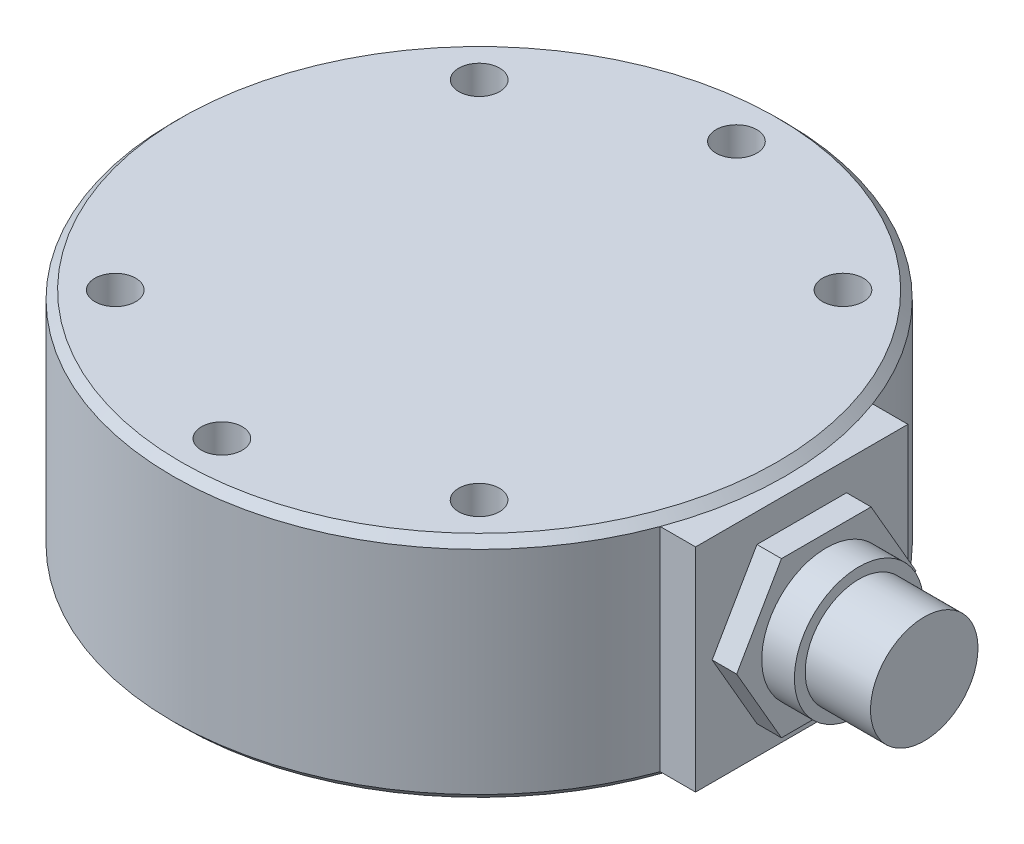
SolidWorks part; units mm, degrees
ref_plane "Front Plane" through (0, 0, 0) normal (0, 0, 1) x (1, 0, 0)
ref_plane "Top Plane" through (0, 0, 0) normal (0, 1, 0) x (1, 0, 0)
ref_plane "Right Plane" through (0, 0, 0) normal (1, 0, 0) x (0, 0, -1)
sketch "Sketch1" plane through (0, 0, 0) normal (0, 1, 0) x (1, 0, 0)
  circle A0 centre (0, 0) radius 37.5
  dimension "D1" = 75
extrude "Boss-Extrude1" add sketch "Sketch1" along normal blind 28
chamfer "Chamfer1" distance 1 angle 45 2 edges at (0, 0, 37.5) (0, 28, 37.5)
ref_plane "Plane1" through (39.5, 0, 0) normal (1, 0, 0) x (0, 0, -1)
sketch "Sketch2" plane through (39.5, 0, 0) normal (1, 0, 0) x (0, 0, -1)
  line L1 (-13, 27) -> (13, 27)
  line L2 (-13, 27) -> (-13, 1)
  line L3 (-13, 1) -> (13, 1)
  line L4 (13, 27) -> (13, 1)
  dimension "D1" = 26
  dimension "D2" = 26
  dimension "D3" = 1
  dimension "D4" = 13
extrude "Boss-Extrude2" add sketch "Sketch2" against normal up to next
sketch "Sketch3" plane through (39.5, 0, 0) normal (1, 0, 0) x (0, 0, -1)
  line L0 (-13, 14) -> (13, 14) construction
  line L1 (-13, 27) -> (-13, 1) construction
  line L2 (13, 1) -> (13, 27) construction
  line L3 (0, 27) -> (0, 1) construction
  line L4 (13, 27) -> (-13, 27) construction
  line L5 (-13, 1) -> (13, 1) construction
  line L7 (10.97, 14) -> (5.485, 23.5003)
  line L8 (5.485, 23.5003) -> (-5.485, 23.5003)
  line L9 (-5.485, 23.5003) -> (-10.97, 14)
  line L10 (-10.97, 14) -> (-5.485, 4.4997)
  line L11 (-5.485, 4.4997) -> (5.485, 4.4997)
  line L12 (5.485, 4.4997) -> (10.97, 14)
  circle A0 centre (0, 14) radius 9.5003 construction
  dimension "D1" = 10.97
extrude "Boss-Extrude3" add sketch "Sketch3" along normal blind 3
sketch "Sketch4" plane through (42.5, 0, 0) normal (1, 0, 0) x (0, 0, -1)
  line L0 (-10.97, 14) -> (10.97, 14) construction
  circle A0 centre (0, 14) radius 7.9
  dimension "D1" = 15.8
extrude "Boss-Extrude4" add sketch "Sketch4" along normal blind 4
sketch "Sketch5" plane through (46.5, 0, 0) normal (1, 0, 0) x (0, 0, -1)
  circle A0 centre (0, 14) radius 6.58
  dimension "D1" = 13.16
extrude "Boss-Extrude5" add sketch "Sketch5" along normal blind 8
sketch "Sketch6" plane through (0, 28, 0) normal (0, 1, 0) x (1, 0, 0)
  circle A0 centre (0, 0) radius 31.5 construction
  circle A1 centre (0, 31.5) radius 2.5
  circle A2 centre (0, -31.5) radius 2.5
  circle A3 centre (22.27, -22.2777) radius 2.5
  circle A4 centre (-22.27, -22.2777) radius 2.5
  circle A5 centre (-22.27, 22.2777) radius 2.5
  circle A6 centre (22.27, 22.2777) radius 2.5
  dimension "D1" = 63
  dimension "D6" = 5
  dimension "D2" = 22.27
  dimension "D3" = 22.27
  dimension "D4" = 22.27
  dimension "D5" = 22.27
extrude "Cut-Extrude1" cut sketch "Sketch6" against normal blind 5
sketch "Sketch7" plane through (0, 0, 0) normal (0, -1, 0) x (1, 0, 0)
  line L0 (0, 0) -> (-36.5, 0) construction
  circle A1 centre (0, 0) radius 36.5
  circle A2 centre (0, 0) radius 36.5 construction
  dimension "D1" = 0
